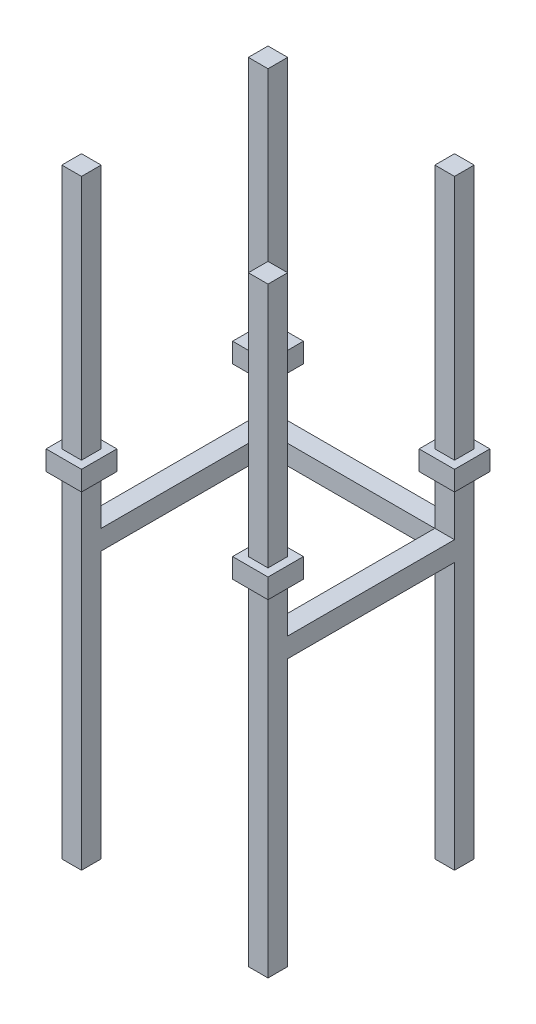
SolidWorks part; units mm, degrees
ref_plane "Alzado" through (0, 0, 0) normal (0, 0, 1) x (1, 0, 0)
ref_plane "Planta" through (0, 0, 0) normal (0, 1, 0) x (1, 0, 0)
ref_plane "Vista lateral" through (0, 0, 0) normal (1, 0, 0) x (0, 0, -1)
sketch "Croquis1" plane through (0, 0, 0) normal (0, 1, 0) x (1, 0, 0)
  line L0 (0, 300) -> (0, -300) construction
  line L1 (-212.132, 212.132) -> (212.132, 212.132) construction
  line L2 (-212.132, 212.132) -> (-212.132, -212.132) construction
  line L3 (-212.132, -212.132) -> (212.132, -212.132) construction
  line L4 (212.132, 212.132) -> (212.132, -212.132) construction
  line L5 (-212.132, 212.132) -> (212.132, -212.132) construction
  line L6 (-212.132, -212.132) -> (212.132, 212.132) construction
  line L7 (-212.132, 212.132) -> (-262.132, 212.132)
  line L8 (-212.132, 212.132) -> (-212.132, 262.132)
  line L9 (-212.132, 262.132) -> (-262.132, 262.132)
  line L10 (-262.132, 212.132) -> (-262.132, 262.132)
  line L11 (262.132, 212.132) -> (262.132, 262.132)
  line L12 (212.132, 262.132) -> (262.132, 262.132)
  line L13 (212.132, 212.132) -> (212.132, 262.132)
  line L14 (212.132, 212.132) -> (262.132, 212.132)
  line L15 (-300, 0) -> (300, 0) construction
  line L16 (-262.132, -212.132) -> (-262.132, -262.132)
  line L17 (-212.132, -262.132) -> (-262.132, -262.132)
  line L18 (-212.132, -212.132) -> (-212.132, -262.132)
  line L19 (-212.132, -212.132) -> (-262.132, -212.132)
  line L20 (212.132, -212.132) -> (262.132, -212.132)
  line L21 (212.132, -212.132) -> (212.132, -262.132)
  line L22 (212.132, -262.132) -> (262.132, -262.132)
  line L23 (262.132, -212.132) -> (262.132, -262.132)
  circle A0 centre (0, 0) radius 300 construction
  dimension "D1" = 600
  dimension "D2" = 50
  dimension "D3" = 50
extrude "Saliente-Extruir1" add sketch "Croquis1" against normal blind 625
sketch "Croquis2" plane through (0, -625, 0) normal (0, -1, 0) x (1, 0, 0)
  line L0 (0, 307.8427) -> (0, -307.8427) construction
  line L1 (-282.132, 282.132) -> (-192.132, 282.132)
  line L2 (-282.132, 282.132) -> (-282.132, 192.132)
  line L3 (-282.132, 192.132) -> (-192.132, 192.132)
  line L4 (-192.132, 282.132) -> (-192.132, 192.132)
  line L5 (-282.132, 282.132) -> (-192.132, 192.132) construction
  line L6 (-282.132, 192.132) -> (-192.132, 282.132) construction
  line L7 (-307.361, 0) -> (310.4962, 0) construction
  line L8 (282.132, 192.132) -> (192.132, 282.132) construction
  line L9 (282.132, 282.132) -> (192.132, 192.132) construction
  line L10 (192.132, 282.132) -> (192.132, 192.132)
  line L11 (282.132, 192.132) -> (192.132, 192.132)
  line L12 (282.132, 282.132) -> (282.132, 192.132)
  line L13 (282.132, 282.132) -> (192.132, 282.132)
  line L14 (282.132, -282.132) -> (192.132, -192.132) construction
  line L15 (282.132, -192.132) -> (192.132, -282.132) construction
  line L16 (282.132, -282.132) -> (192.132, -282.132)
  line L17 (282.132, -282.132) -> (282.132, -192.132)
  line L18 (282.132, -192.132) -> (192.132, -192.132)
  line L19 (192.132, -282.132) -> (192.132, -192.132)
  line L20 (-282.132, -192.132) -> (-192.132, -282.132) construction
  line L21 (-282.132, -282.132) -> (-192.132, -192.132) construction
  line L22 (-192.132, -282.132) -> (-192.132, -192.132)
  line L23 (-282.132, -192.132) -> (-192.132, -192.132)
  line L24 (-282.132, -282.132) -> (-282.132, -192.132)
  line L25 (-282.132, -282.132) -> (-192.132, -282.132)
  line L27 (212.132, 212.132) -> (-212.132, 212.132) construction
  line L28 (212.132, 212.132) -> (212.132, -212.132) construction
  line L29 (212.132, -212.132) -> (-212.132, -212.132) construction
  line L30 (-212.132, 212.132) -> (-212.132, -212.132) construction
  line L31 (212.132, 212.132) -> (-212.132, -212.132) construction
  line L32 (212.132, -212.132) -> (-212.132, 212.132) construction
  line L33 (237.132, -237.132) -> (-237.132, -237.132) construction
  line L34 (237.132, -237.132) -> (237.132, 237.132) construction
  line L35 (237.132, 237.132) -> (-237.132, 237.132) construction
  line L36 (-237.132, -237.132) -> (-237.132, 237.132) construction
  circle A0 centre (0, 0) radius 300 construction
  point P0 (-237.132, 237.132)
  point P14 (237.132, 237.132)
  point P19 (237.132, -237.132)
  point P24 (-237.132, -237.132)
  dimension "D3" = 600
  dimension "D1" = 90
  dimension "D2" = 90
extrude "Saliente-Extruir2" add sketch "Croquis2" along normal blind 50
sketch "Croquis4" plane through (0, -675, 0) normal (0, -1, 0) x (1, 0, 0)
  line L0 (0, -282.8427) -> (0, 282.8427) construction
  line L1 (-212.132, 212.132) -> (-262.132, 212.132)
  line L2 (-212.132, 212.132) -> (-212.132, 262.132)
  line L3 (-212.132, 262.132) -> (-262.132, 262.132)
  line L4 (-262.132, 212.132) -> (-262.132, 262.132)
  line L5 (-275.9995, 0) -> (282.8427, 0) construction
  line L6 (-262.132, -212.132) -> (-262.132, -262.132)
  line L7 (-212.132, -262.132) -> (-262.132, -262.132)
  line L8 (-212.132, -212.132) -> (-212.132, -262.132)
  line L9 (-212.132, -212.132) -> (-262.132, -212.132)
  line L10 (262.132, 212.132) -> (262.132, 262.132)
  line L11 (212.132, 262.132) -> (262.132, 262.132)
  line L12 (212.132, 212.132) -> (212.132, 262.132)
  line L13 (212.132, 212.132) -> (262.132, 212.132)
  line L14 (212.132, -212.132) -> (262.132, -212.132)
  line L15 (212.132, -212.132) -> (212.132, -262.132)
  line L16 (212.132, -262.132) -> (262.132, -262.132)
  line L17 (262.132, -212.132) -> (262.132, -262.132)
extrude "Saliente-Extruir3" add sketch "Croquis4" along normal blind 853
ref_plane "Plano1" through (0, -800, 0) normal (0, 1, 0) x (1, 0, 0)
sketch "Croquis6" plane through (0, -800, 0) normal (0, 1, 0) x (1, 0, 0)
  line L21 (262.132, -262.132) -> (262.132, -212.132) construction
  line L30 (-262.132, 262.132) -> (262.132, 262.132)
  line L31 (-262.132, 262.132) -> (-262.132, -262.132)
  line L32 (-262.132, -262.132) -> (-212.132, -262.132)
  line L33 (262.132, 262.132) -> (262.132, -262.132)
  line L34 (262.132, -262.132) -> (262.132, -212.132) construction
  line L35 (-212.132, -212.132) -> (-212.132, -262.132)
  line L36 (-212.132, 212.132) -> (212.132, 212.132)
  line L37 (-212.132, 212.132) -> (-212.132, -212.132)
  line L39 (212.132, 212.132) -> (212.132, -212.132)
  line L40 (212.132, -212.132) -> (212.132, -262.132)
  line L41 (212.132, -212.132) -> (212.132, -262.132) construction
  line L42 (212.132, -262.132) -> (262.132, -262.132)
extrude "Saliente-Extruir4" add sketch "Croquis6" against normal blind 50
